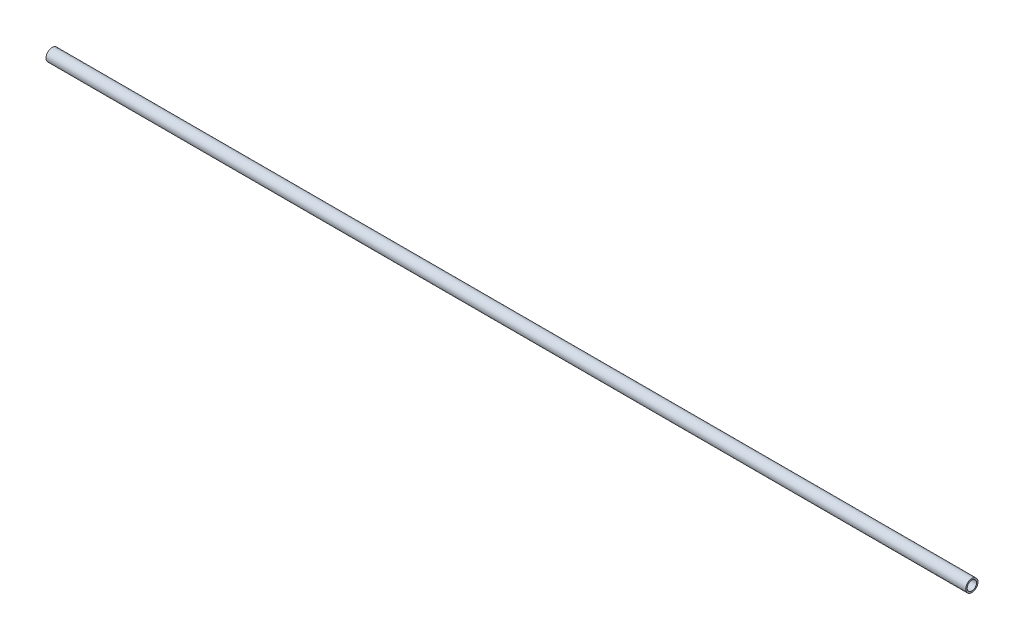
SolidWorks part; units mm, degrees
material "AISI 4130 Steel, annealed at 865C"
ref_plane "Front Plane" through (0, 0, 0) normal (0, 0, 1) x (1, 0, 0)
ref_plane "Top Plane" through (0, 0, 0) normal (0, 1, 0) x (1, 0, 0)
ref_plane "Right Plane" through (0, 0, 0) normal (1, 0, 0) x (0, 0, -1)
sketch "Sketch1" plane through (0, 0, 0) normal (1, 0, 0) x (0, 0, -1)
  circle A0 centre (0, 0) radius 12.7
  circle A1 centre (0, 0) radius 9.652
  dimension "D1" = 25.4
  dimension "D2" = 19.304
extrude "Boss-Extrude1" add sketch "Sketch1" along normal blind 1905
